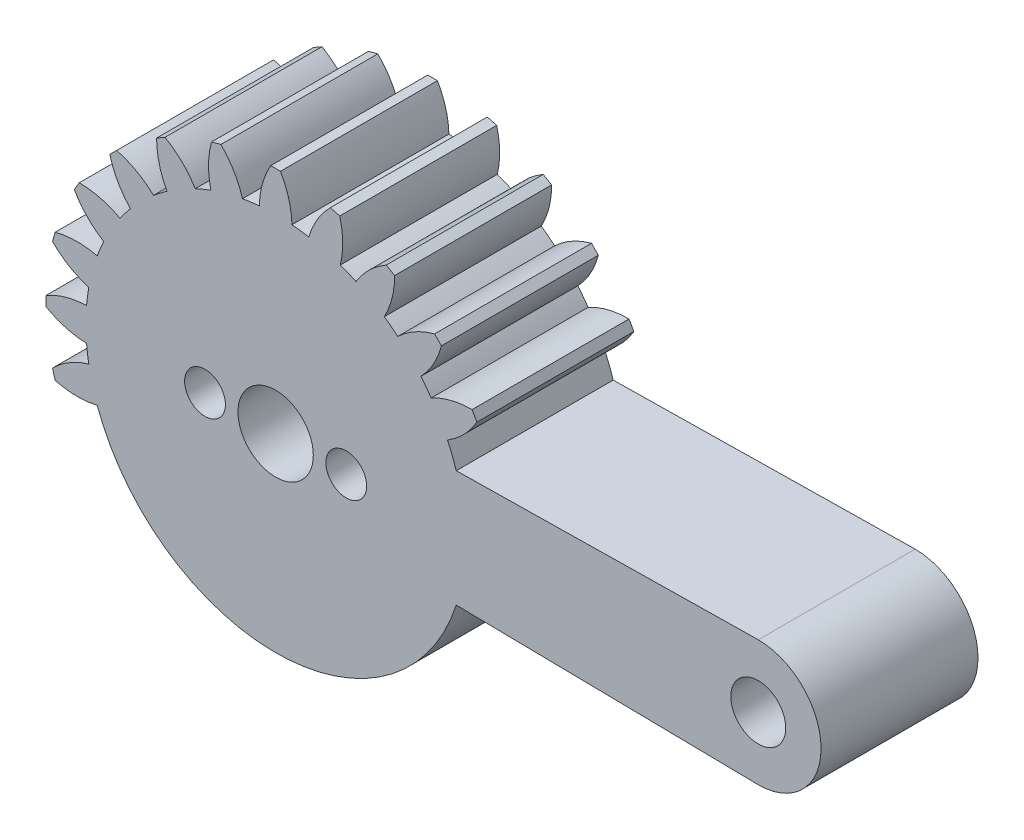
SolidWorks part; units mm, degrees
ref_plane "Front Plane" through (0, 0, 0) normal (0, 0, 1) x (1, 0, 0)
ref_plane "Top Plane" through (0, 0, 0) normal (0, 1, 0) x (1, 0, 0)
ref_plane "Right Plane" through (0, 0, 0) normal (1, 0, 0) x (0, 0, -1)
sketch "Sketch1" plane through (0, 0, 0) normal (0, 0, 1) x (1, 0, 0)
  line L0 (0, 0) -> (30.75, 0) construction
  line L1 (0, -14.63) -> (0, 14.63) construction
  line L2 (-0.31, 14.63) -> (0.31, 14.63)
  line L3 (3.4871, 14.2117) -> (4.086, 14.0513)
  line L4 (7.0465, 12.825) -> (7.5835, 12.515)
  line L5 (10.1258, 10.5642) -> (10.5642, 10.1258)
  line L6 (12.515, 7.5835) -> (12.825, 7.0465)
  line L7 (14.1422, 3.7467) -> (14.2117, 3.4871)
  line L8 (14.63, 0.31) -> (14.63, -0.31)
  line L9 (14.2117, -3.4871) -> (14.1422, -3.7467)
  line L10 (12.825, -7.0465) -> (12.515, -7.5835)
  line L11 (10.5642, -10.1258) -> (10.1258, -10.5642)
  line L12 (7.5835, -12.515) -> (7.0465, -12.825)
  line L13 (4.086, -14.0513) -> (3.4871, -14.2117)
  line L14 (0.31, -14.63) -> (-0.31, -14.63)
  line L15 (-3.4871, -14.2117) -> (-4.086, -14.0513)
  line L16 (-7.0465, -12.825) -> (-7.5835, -12.515)
  line L17 (-10.1258, -10.5642) -> (-10.5642, -10.1258)
  line L18 (-12.515, -7.5835) -> (-12.825, -7.0465)
  line L19 (-14.0513, -4.086) -> (-14.2117, -3.4871)
  line L20 (-14.63, -0.31) -> (-14.63, 0.31)
  line L21 (-14.2117, 3.4871) -> (-14.0513, 4.086)
  line L22 (-12.825, 7.0465) -> (-12.515, 7.5835)
  line L23 (-10.5642, 10.1258) -> (-10.1258, 10.5642)
  line L24 (-7.5835, 12.515) -> (-7.0465, 12.825)
  line L25 (-4.086, 14.0513) -> (-3.4871, 14.2117)
  line L26 (30.75, -4) -> (30.75, 4) construction
  line L27 (30.75, 4) -> (11.5078, 3.7065)
  line L28 (30.75, -4) -> (11.5078, -3.7065)
  circle A0 centre (0, 0) radius 1.75
  circle A1 centre (0, 0) radius 12.09
  circle A2 centre (30.75, 0) radius 1.75
  arc A3 (-1.04, 12.0452) -> (-0.31, 14.63) centre (4.3585, 11.9161) cw
  arc A4 (1.04, 12.0452) -> (0.31, 14.63) centre (-4.3585, 11.9161) ccw
  arc A5 (2.113, 11.9039) -> (3.4871, 14.2117) centre (7.294, 10.382) cw
  arc A6 (4.1221, 11.3656) -> (4.086, 14.0513) centre (-1.1258, 12.6381) ccw
  arc A7 (5.1219, 10.9514) -> (7.0465, 12.825) centre (9.7326, 8.1404) cw
  arc A8 (6.9233, 9.9114) -> (7.5835, 12.515) centre (2.1835, 12.4988) ccw
  arc A9 (7.7818, 9.2526) -> (10.1258, 10.5642) centre (11.5078, 5.344) cw
  arc A10 (9.2526, 7.7818) -> (10.5642, 10.1258) centre (5.344, 11.5078) ccw
  arc A11 (9.9114, 6.9233) -> (12.515, 7.5835) centre (12.4988, 2.1835) cw
  arc A12 (10.9514, 5.1219) -> (12.825, 7.0465) centre (8.1404, 9.7326) ccw
  arc A14 (11.9039, 2.113) -> (14.2117, 3.4871) centre (10.382, 7.294) ccw
  arc A15 (12.0452, 1.04) -> (14.63, 0.31) centre (11.9161, -4.3585) cw
  arc A16 (12.0452, -1.04) -> (14.63, -0.31) centre (11.9161, 4.3585) ccw
  arc A17 (11.9039, -2.113) -> (14.2117, -3.4871) centre (10.382, -7.294) cw
  arc A19 (10.9514, -5.1219) -> (12.825, -7.0465) centre (8.1404, -9.7326) cw
  arc A20 (9.9114, -6.9233) -> (12.515, -7.5835) centre (12.4988, -2.1835) ccw
  arc A21 (9.2526, -7.7818) -> (10.5642, -10.1258) centre (5.344, -11.5078) cw
  arc A22 (7.7818, -9.2526) -> (10.1258, -10.5642) centre (11.5078, -5.344) ccw
  arc A23 (6.9233, -9.9114) -> (7.5835, -12.515) centre (2.1835, -12.4988) cw
  arc A24 (5.1219, -10.9514) -> (7.0465, -12.825) centre (9.7326, -8.1404) ccw
  arc A25 (4.1221, -11.3656) -> (4.086, -14.0513) centre (-1.1258, -12.6381) cw
  arc A26 (2.113, -11.9039) -> (3.4871, -14.2117) centre (7.294, -10.382) ccw
  arc A27 (1.04, -12.0452) -> (0.31, -14.63) centre (-4.3585, -11.9161) cw
  arc A28 (-1.04, -12.0452) -> (-0.31, -14.63) centre (4.3585, -11.9161) ccw
  arc A29 (-2.113, -11.9039) -> (-3.4871, -14.2117) centre (-7.294, -10.382) cw
  arc A30 (-4.1221, -11.3656) -> (-4.086, -14.0513) centre (1.1258, -12.6381) ccw
  arc A31 (-5.1219, -10.9514) -> (-7.0465, -12.825) centre (-9.7326, -8.1404) cw
  arc A32 (-6.9233, -9.9114) -> (-7.5835, -12.515) centre (-2.1835, -12.4988) ccw
  arc A33 (-7.7818, -9.2526) -> (-10.1258, -10.5642) centre (-11.5078, -5.344) cw
  arc A34 (-9.2526, -7.7818) -> (-10.5642, -10.1258) centre (-5.344, -11.5078) ccw
  arc A35 (-9.9114, -6.9233) -> (-12.515, -7.5835) centre (-12.4988, -2.1835) cw
  arc A36 (-10.9514, -5.1219) -> (-12.825, -7.0465) centre (-8.1404, -9.7326) ccw
  arc A37 (-11.3656, -4.1221) -> (-14.0513, -4.086) centre (-12.6381, 1.1258) cw
  arc A38 (-11.9039, -2.113) -> (-14.2117, -3.4871) centre (-10.382, -7.294) ccw
  arc A39 (-12.0452, -1.04) -> (-14.63, -0.31) centre (-11.9161, 4.3585) cw
  arc A40 (-12.0452, 1.04) -> (-14.63, 0.31) centre (-11.9161, -4.3585) ccw
  arc A41 (-11.9039, 2.113) -> (-14.2117, 3.4871) centre (-10.382, 7.294) cw
  arc A42 (-11.3656, 4.1221) -> (-14.0513, 4.086) centre (-12.6381, -1.1258) ccw
  arc A43 (-10.9514, 5.1219) -> (-12.825, 7.0465) centre (-8.1404, 9.7326) cw
  arc A44 (-9.9114, 6.9233) -> (-12.515, 7.5835) centre (-12.4988, 2.1835) ccw
  arc A45 (-9.2526, 7.7818) -> (-10.5642, 10.1258) centre (-5.344, 11.5078) cw
  arc A46 (-7.7818, 9.2526) -> (-10.1258, 10.5642) centre (-11.5078, 5.344) ccw
  arc A47 (-6.9233, 9.9114) -> (-7.5835, 12.515) centre (-2.1835, 12.4988) cw
  arc A48 (-5.1219, 10.9514) -> (-7.0465, 12.825) centre (-9.7326, 8.1404) ccw
  arc A49 (-4.1221, 11.3656) -> (-4.086, 14.0513) centre (1.1258, 12.6381) cw
  arc A50 (-2.113, 11.9039) -> (-3.4871, 14.2117) centre (-7.294, 10.382) ccw
  arc A51 (30.75, -4) -> (30.75, 4) centre (30.75, 0) ccw
  arc A53 (11.3656, 4.1221) -> (14.0513, 4.086) centre (12.6381, -1.1258) cw [skipped]
  arc A54 (11.3656, -4.1221) -> (14.0513, -4.086) centre (12.6381, 1.1258) ccw [skipped]
  point P9 (0, 0)
  point P157 (30.75, 0)
  dimension "D2" = 3.5
  dimension "D3" = 24.18
  dimension "D4" = 3.5
  dimension "D6" = 5.4
  dimension "D10" = 8
  dimension "D1" = 30.75
  dimension "D5" = 29.26
  dimension "D7" = 0.31
  dimension "D8" = 1.04
  dimension "D9" = 24
extrude "Boss-Extrude1" add sketch "Sketch1" along normal blind 10 contours A1 A0 | L28 A51 L27 L7 A14 A1 A15 L8 A16 A17 L9 A2 | A1 A38 L19 A37 | A1 A40 L20 A39 | A1 A42 L21 A41 | A1 A44 L22 A43 | A1 A46 L23 A45 | A1 A48 L24 A47 | A1 A50 L25 A49 | A1 A4 L2 A3 | A1 A6 L3 A5 | A1 A8 L4 A7 | A1 A10 L5 A9 | A1 A12 L6 A11 | A1 A14 L7 L27 | A1 A16 L8 A15 | A17 A1 L28 L9
sketch "Sketch2" plane through (0, 0, 10) normal (0, 0, 1) x (1, 0, 0)
  line L0 (-4.5, 0) -> (4.5, 0) construction
  circle A0 centre (0, 0) radius 2.4
  circle A1 centre (4.5, 0) radius 1.3
  circle A2 centre (-4.5, 0) radius 1.3
  point P5 (0, 0)
  dimension "D2" = 2.6
  dimension "D3" = 4.8
  dimension "D1" = 9
extrude "Cut-Extrude1" cut sketch "Sketch2" against normal through all
